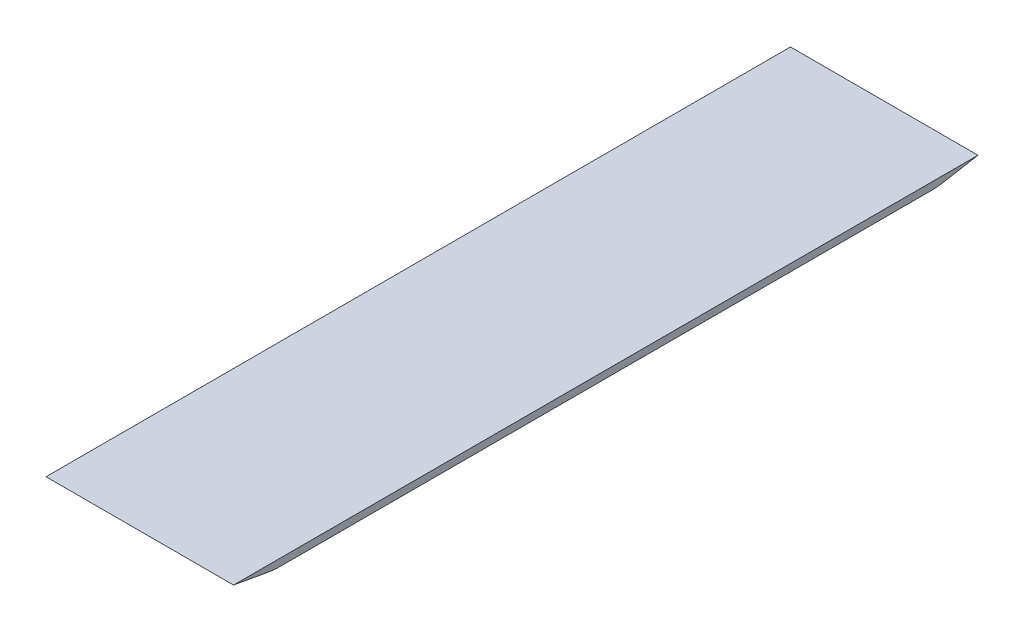
SolidWorks part; units mm, degrees
ref_plane "Front Plane" through (0, 0, 0) normal (0, 0, 1) x (1, 0, 0)
ref_plane "Top Plane" through (0, 0, 0) normal (0, 1, 0) x (1, 0, 0)
ref_plane "Right Plane" through (0, 0, 0) normal (1, 0, 0) x (0, 0, -1)
sketch "Sketch1" plane through (0, 0, 0) normal (1, 0, 0) x (0, 0, -1)
  line L20 (28, -5) -> (488, -5)
  line L21 (488, -5) -> (516, 0)
  line L37 (0, 0) -> (516, 0)
  line L38 (0, 0) -> (28, -5)
  dimension "D1" = 28
  dimension "D2" = 460
  dimension "D3" = 5
  dimension "D8" = 28
extrude "Boss-Extrude1" add sketch "Sketch1" along normal blind 130 contours L20 L21 L37 L38
fillet "Fillet1" radius 50 2 edges at (65, -5, -488) (65, -5, -28)
